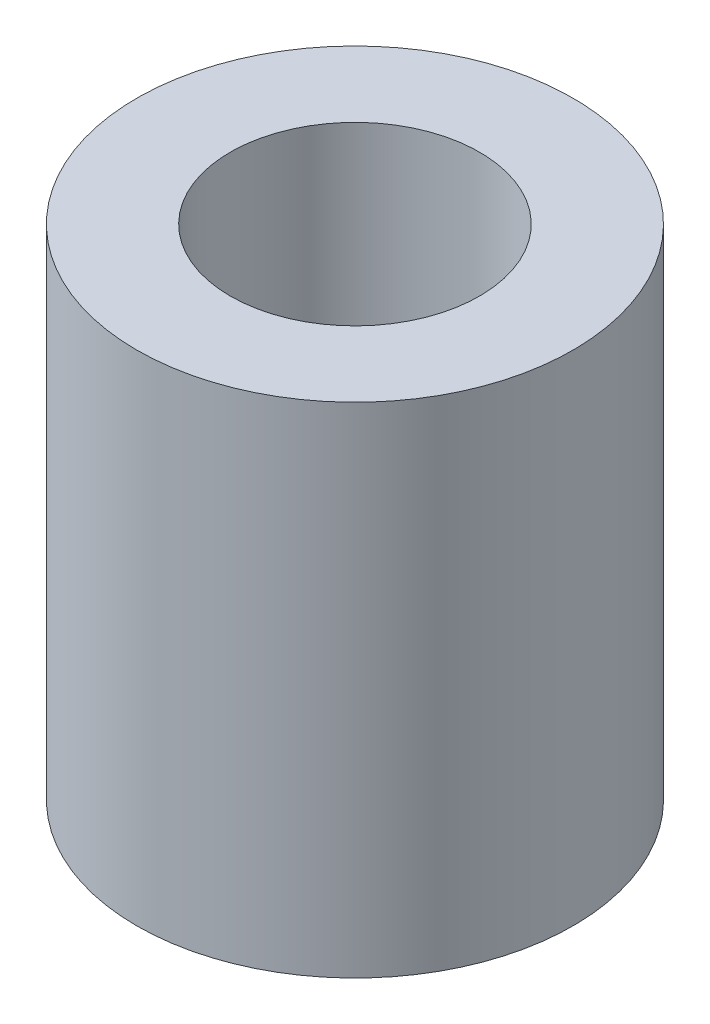
SolidWorks part; units mm, degrees
ref_plane "Front Plane" through (0, 0, 0) normal (0, 0, 1) x (1, 0, 0)
ref_plane "Top Plane" through (0, 0, 0) normal (0, 1, 0) x (1, 0, 0)
ref_plane "Right Plane" through (0, 0, 0) normal (1, 0, 0) x (0, 0, -1)
sketch "Sketch1" plane through (0, 0, 0) normal (0, 1, 0) x (1, 0, 0)
  circle A0 centre (0, 0) radius 2.7781
  dimension "D1" = 5.5562
extrude "Boss-Extrude1" add sketch "Sketch1" along normal blind 6.35
sketch "Sketch2" plane through (0, 6.35, 0) normal (0, 1, 0) x (1, 0, 0)
  circle A0 centre (0, 0) radius 1.5875
  dimension "D1" = 3.175
extrude "Cut-Extrude1" cut sketch "Sketch2" against normal blind 6.35
